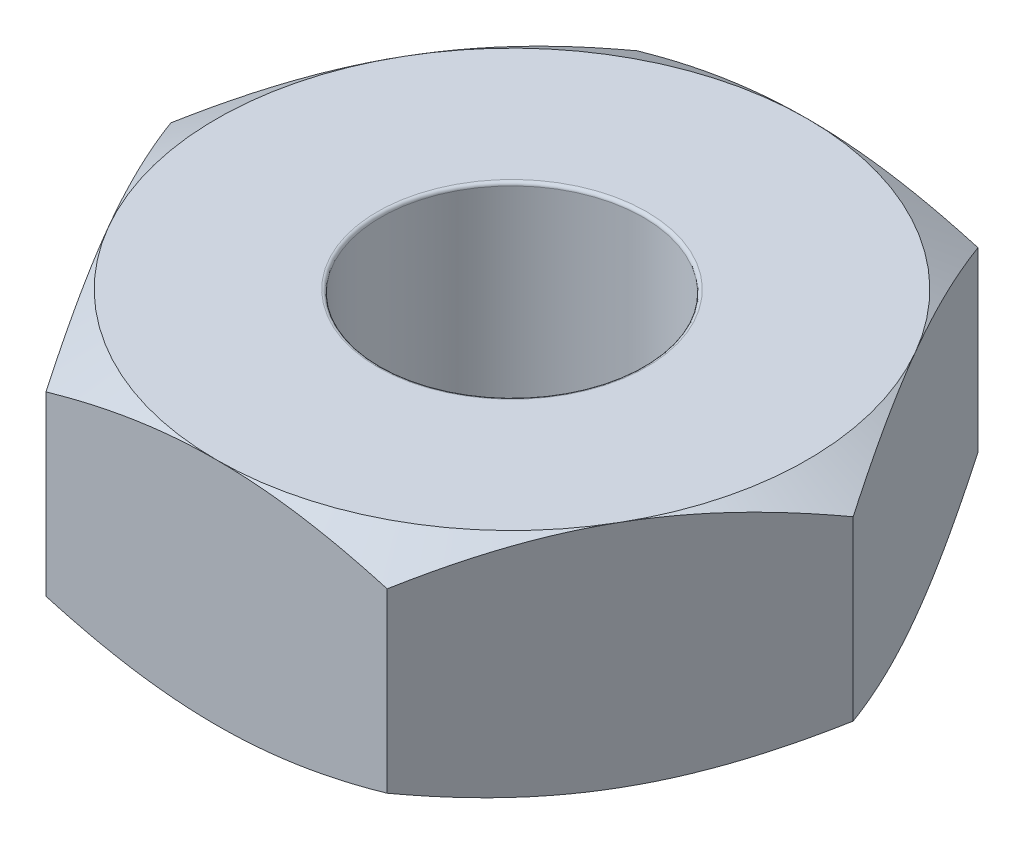
SolidWorks part; units mm, degrees
ref_plane "Front Plane" through (0, 0, 0) normal (0, 0, 1) x (1, 0, 0)
ref_plane "Top Plane" through (0, 0, 0) normal (0, 1, 0) x (1, 0, 0)
ref_plane "Right Plane" through (0, 0, 0) normal (1, 0, 0) x (0, 0, -1)
sketch "Sketch1" plane through (0, 0, 0) normal (0, 1, 0) x (1, 0, 0)
  line L1 (1.299, -2.25) -> (2.5981, 0)
  line L2 (2.5981, 0) -> (1.299, 2.25)
  line L3 (1.299, 2.25) -> (-1.299, 2.25)
  line L4 (-1.299, 2.25) -> (-2.5981, 0)
  line L5 (-2.5981, 0) -> (-1.299, -2.25)
  line L6 (-1.299, -2.25) -> (1.299, -2.25)
  circle A0 centre (0, 0) radius 1
  circle A1 centre (0, 0) radius 2.25 construction
  point P3 (0, 2.25)
  dimension "D1" = 2
  dimension "D2" = 4.5
extrude "Boss-Extrude1" add sketch "Sketch1" along normal blind 1.75
sketch "Sketch2" plane through (0, 1.75, 0) normal (0, 1, 0) x (1, 0, 0)
  circle A0 centre (0, 0) radius 2.25 construction
  circle A1 centre (0, 0) radius 2.25
extrude "Cut-Extrude1" cut sketch "Sketch2" against normal blind 1.75 draft 60 flip side to cut
sketch "Sketch3" plane through (0, 0, 0) normal (0, -1, 0) x (1, 0, 0)
  circle A0 centre (0, 0) radius 2.25 construction
  circle A1 centre (0, 0) radius 2.25
extrude "Cut-Extrude2" cut sketch "Sketch3" against normal blind 1.75 draft 60 flip side to cut
fillet "Fillet1" radius 0.025 2 edges at (0, 0, 1) (0, 1.75, 1)
